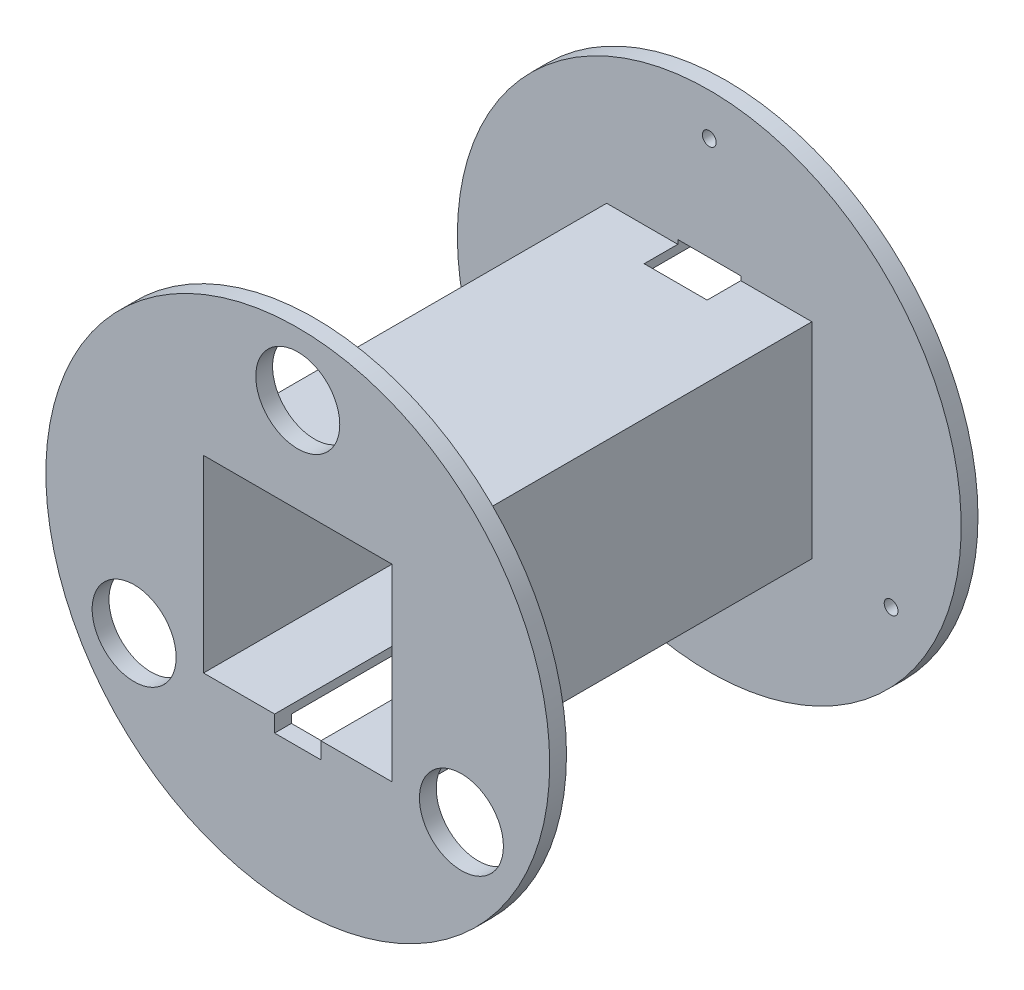
SolidWorks part; units mm, degrees
ref_plane "Front Plane" through (0, 0, 0) normal (0, 0, 1) x (1, 0, 0)
ref_plane "Top Plane" through (0, 0, 0) normal (0, 1, 0) x (1, 0, 0)
ref_plane "Right Plane" through (0, 0, 0) normal (1, 0, 0) x (0, 0, -1)
sketch "Sketch1" plane through (0, 0, 0) normal (0, 0, 1) x (1, 0, 0)
  circle A0 centre (0, 0) radius 76.2
  dimension "D1" = 152.4
extrude "Boss-Extrude1" add sketch "Sketch1" along normal blind 129.54
sketch "Sketch2" plane through (0, 0, 0) normal (0, 0, -1) x (-1, 0, 0)
  line L1 (31.04, -31.04) -> (-31.04, -31.04)
  line L2 (31.04, -31.04) -> (31.04, 31.04)
  line L3 (31.04, 31.04) -> (-31.04, 31.04)
  line L4 (-31.04, -31.04) -> (-31.04, 31.04)
  line L5 (31.04, -31.04) -> (-31.04, 31.04) construction
  line L6 (31.04, 31.04) -> (-31.04, -31.04) construction
  circle A0 centre (0, 0) radius 76.2
  point P0 (0, 0)
  circle M5 centre (0, 0) radius 76.2
  dimension "D1" = 62.08
extrude "Cut-Extrude1" cut sketch "Sketch2" against normal offset from surface (119.38 mm away) 5.08 from offset 5.08 contours L1 L4 L3 L2 M5 | L4 L1 L2 L3 offset against normal yes
sketch "Sketch3" plane through (0, 0, 0) normal (0, 0, -1) x (-1, 0, 0)
  line L1 (28.5, -28.5) -> (-28.5, -28.5)
  line L2 (28.5, -28.5) -> (28.5, 28.5)
  line L3 (28.5, 28.5) -> (-28.5, 28.5)
  line L4 (-28.5, -28.5) -> (-28.5, 28.5)
  line L5 (28.5, -28.5) -> (-28.5, 28.5) construction
  line L6 (28.5, 28.5) -> (-28.5, -28.5) construction
  point P0 (0, 0)
  dimension "D1" = 57
extrude "Cut-Extrude2" cut sketch "Sketch3" against normal up to surface (129.54 mm away) up to face at (76.2, 0, 129.54)
sketch "Sketch4" plane through (0, 0, 0) normal (0, 0, -1) x (-1, 0, 0)
  circle A0 centre (0, 63.5) radius 2.0828
  circle A1 centre (0, 0) radius 76.2 construction
  circle A2 centre (54.9926, -31.75) radius 2.0828
  circle A3 centre (-54.9926, -31.75) radius 2.0828
  point P11 (0, 0)
  dimension "D1" = 4.1656
  dimension "D2" = 63.5
  dimension "D3" = 3
extrude "Cut-Extrude3" cut sketch "Sketch4" against normal up to surface (5.08 mm away) up to face at (-76.2, 0, 5.08)
sketch "Sketch5" plane through (0, 0, 129.54) normal (0, 0, 1) x (1, 0, 0)
  circle A0 centre (0, 57.15) radius 12.7
  circle A1 centre (49.4934, -28.575) radius 12.7
  circle A2 centre (-49.4934, -28.575) radius 12.7
  point P9 (0, 0)
  dimension "D1" = 25.4
  dimension "D2" = 57.15
  dimension "D3" = 3
extrude "Cut-Extrude4" cut sketch "Sketch5" against normal up to surface (5.08 mm away) up to face at (76.2, 0, 124.46)
sketch "Sketch8" plane through (0, 0, 129.54) normal (0, 0, 1) x (1, 0, 0)
  line L0 (-7, -28.5) -> (7, -28.5)
  line L1 (28.5, -28.5) -> (-28.5, -28.5) construction
  line L2 (7, -28.5) -> (7, -33.5)
  line L3 (7, -33.5) -> (-7, -33.5)
  line L4 (-7, -33.5) -> (-7, -28.5)
  point P5 (0, -28.5)
  dimension "D1" = 5
  dimension "D2" = 14
extrude "Cut-Extrude5" cut sketch "Sketch8" against normal through all
sketch "Sketch9" plane through (0, 0, 0) normal (0, 0, -1) x (-1, 0, 0)
  line L0 (28.5, 28.5) -> (-28.5, 28.5) construction
  line L1 (9.525, 24.69) -> (-9.525, 24.69)
  line L2 (9.525, 24.69) -> (9.525, 32.31)
  line L3 (9.525, 32.31) -> (-9.525, 32.31)
  line L4 (-9.525, 24.69) -> (-9.525, 32.31)
  line L5 (9.525, 24.69) -> (-9.525, 32.31) construction
  line L6 (9.525, 32.31) -> (-9.525, 24.69) construction
  point P0 (0, 28.5)
  dimension "D1" = 7.62
  dimension "D2" = 19.05
extrude "Cut-Extrude6" cut sketch "Sketch9" against normal blind 15.24
